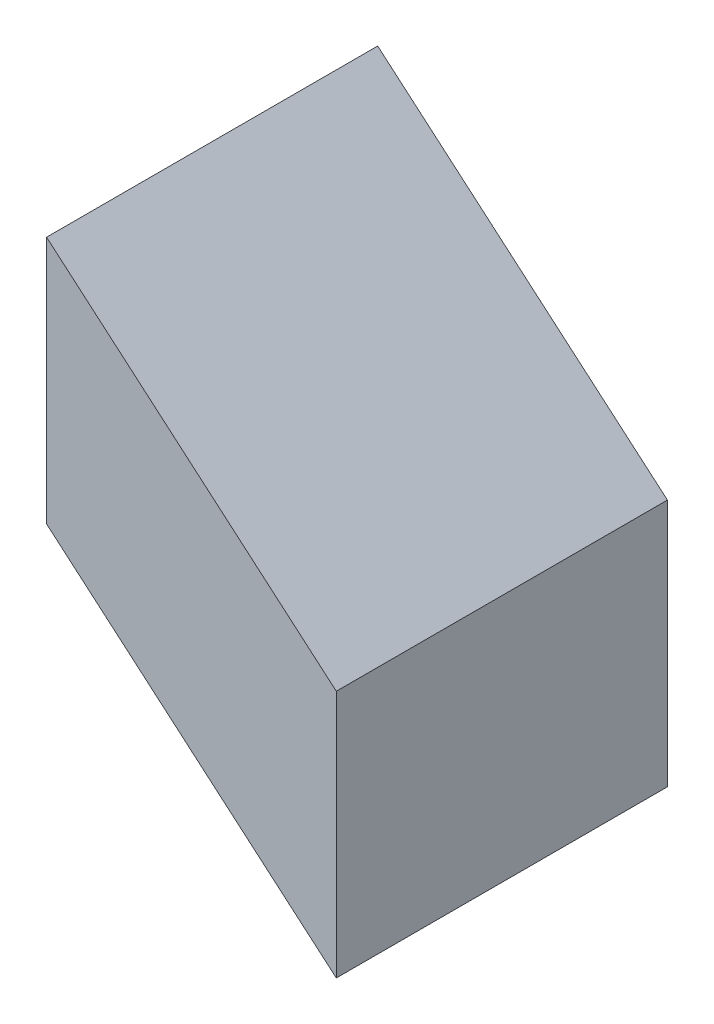
SolidWorks part; units mm, degrees
ref_plane "Front Plane" through (0, 0, 0) normal (0, 0, 1) x (1, 0, 0)
ref_plane "Top Plane" through (0, 0, 0) normal (0, 1, 0) x (1, 0, 0)
ref_plane "Right Plane" through (0, 0, 0) normal (1, 0, 0) x (0, 0, -1)
sketch "Sketch1" plane through (0, 0, 0) normal (0, 0, 1) x (1, 0, 0)
  line L0 (0, 0) -> (0, -38.1)
  line L1 (0, -38.1) -> (-44.45, 0)
  line L2 (-44.45, 0) -> (-44.45, 38.1)
  line L3 (-44.45, 38.1) -> (0, 0)
  line L4 (-44.45, 0) -> (0, 0) construction
  dimension "D1" = 44.45
  dimension "D2" = 38.1
extrude "Boss-Extrude1" add sketch "Sketch1" along normal blind 50.8
